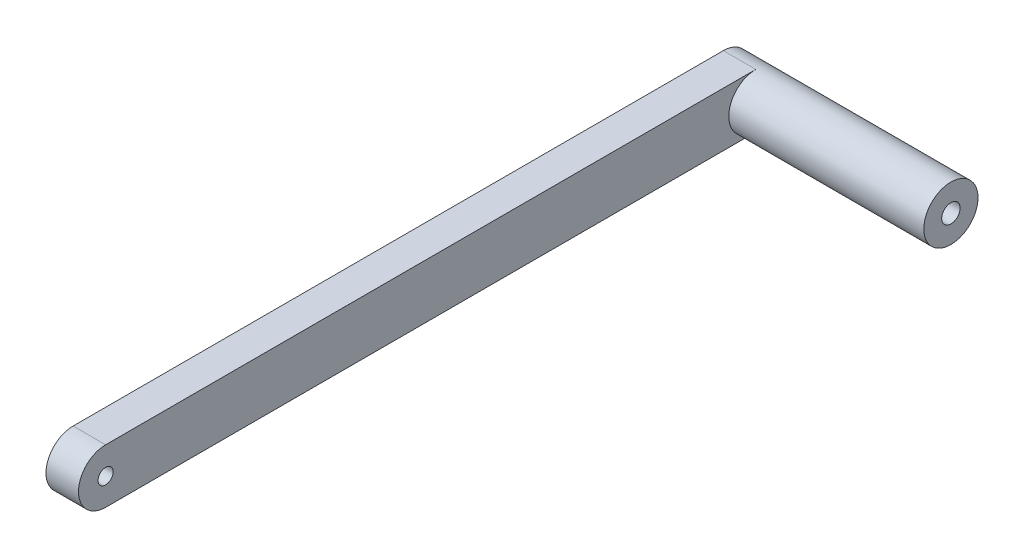
SolidWorks part; units mm, degrees
ref_plane "Plano frontal" through (0, 0, 0) normal (0, 0, 1) x (1, 0, 0)
ref_plane "Plano superior" through (0, 0, 0) normal (0, 1, 0) x (1, 0, 0)
ref_plane "Plano direito" through (0, 0, 0) normal (1, 0, 0) x (0, 0, -1)
sketch "Esboço1" plane through (0, 0, 0) normal (1, 0, 0) x (0, 0, -1)
  line L0 (-30, 0) -> (30, 0) construction
  line L1 (-30, 2.5) -> (30, 2.5)
  line L2 (-30, -2.5) -> (30, -2.5)
  arc A0 (-30, 2.5) -> (-30, -2.5) centre (-30, 0) ccw
  arc A1 (30, -2.5) -> (30, 2.5) centre (30, 0) ccw
  point P3 (0, 0)
  dimension "D1" = 5
  dimension "D2" = 60
extrude "Ressalto-extrusão1" add sketch "Esboço1" along normal blind 3
sketch "Esboço2" plane through (3, 0, 0) normal (1, 0, 0) x (0, 0, -1)
  circle A0 centre (30, 0) radius 2.5
  arc A1 (30, -2.5) -> (30, 2.5) centre (30, 0) ccw construction
extrude "Ressalto-extrusão2" add sketch "Esboço2" along normal blind 18
sketch "Esboço3" plane through (21, 0, 0) normal (1, 0, 0) x (0, 0, -1)
  circle A0 centre (30, 0) radius 0.85
  circle A1 centre (30, 0) radius 2.5 construction
  dimension "D1" = 1.7
extrude "Corte-extrusão1" cut sketch "Esboço3" against normal through all
sketch "Esboço4" plane through (3, 0, 0) normal (1, 0, 0) x (0, 0, -1)
  circle A0 centre (-30, 0) radius 0.7
  arc A1 (-30, 2.5) -> (-30, -2.5) centre (-30, 0) ccw construction
  dimension "D1" = 1.4
extrude "Corte-extrusão2" cut sketch "Esboço4" against normal through all
